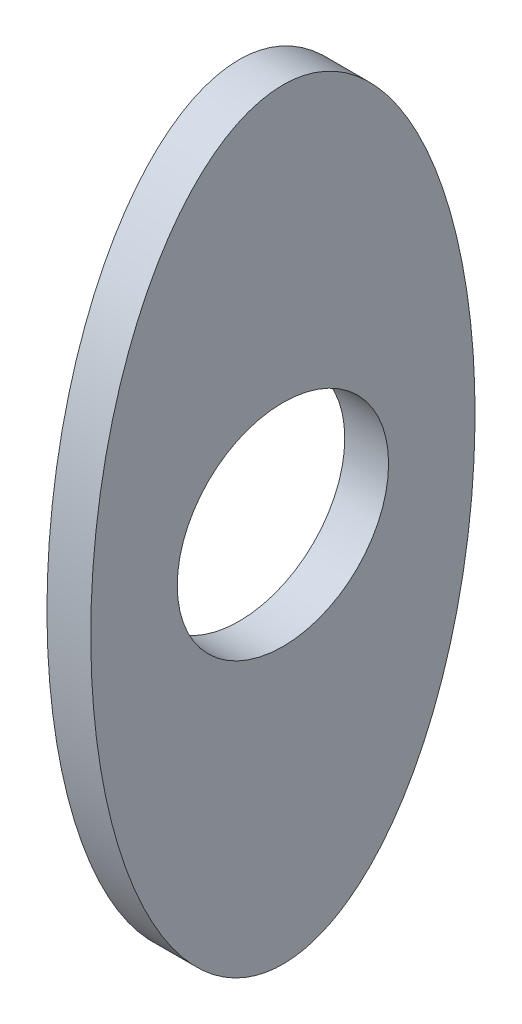
SolidWorks part; units mm, degrees
ref_plane "Alzado" through (0, 0, 0) normal (0, 0, 1) x (1, 0, 0)
ref_plane "Planta" through (0, 0, 0) normal (0, 1, 0) x (1, 0, 0)
ref_plane "Vista lateral" through (0, 0, 0) normal (1, 0, 0) x (0, 0, -1)
sketch "Croquis2" plane through (0, 0, 0) normal (1, 0, 0) x (0, 0, -1)
  ellipse E0 centre (0, 0) end of major axis (0, 26.0743) minor radius 13.1578
extrude "Saliente-Extruir1" add sketch "Croquis2" along normal blind 3
sketch "Croquis3" plane through (3, 0, 0) normal (1, 0, 0) x (0, 0, -1)
  circle A0 centre (0, 0) radius 7.2361
extrude "Cortar-Extruir1" cut sketch "Croquis3" against normal blind 3 contours A0
scale "Escala1" bodies to scale 102 scale about centroid uniform scaling yes scale factor 0.7
scale "Escala2" scale about centroid uniform scaling yes scale factor 1.2
